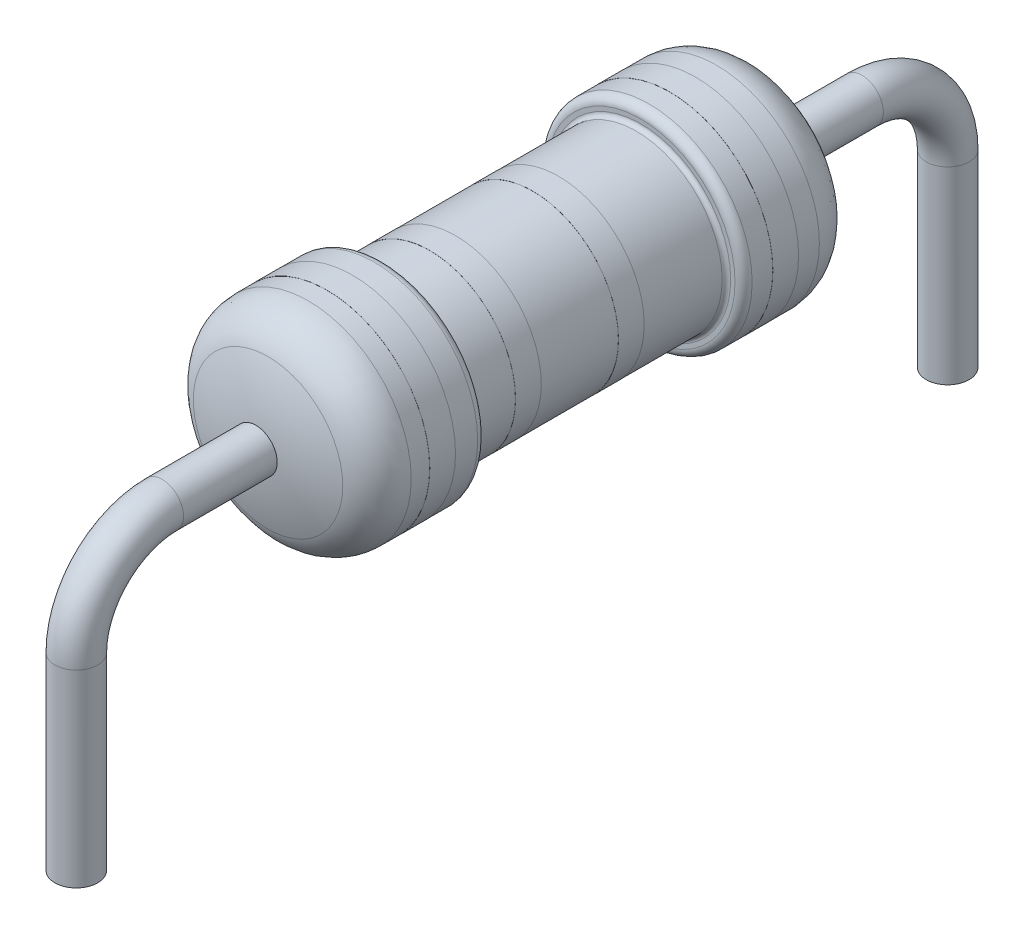
SolidWorks part; units mm, degrees
ref_plane "Plano frontal" through (0, 0, 0) normal (0, 0, 1) x (1, 0, 0)
ref_plane "Plano superior" through (0, 0, 0) normal (0, 1, 0) x (1, 0, 0)
ref_plane "Plano direito" through (0, 0, 0) normal (1, 0, 0) x (0, 0, -1)
sketch "Esboço1" plane through (0, 0, 0) normal (1, 0, 0) x (0, 0, -1)
  line L0 (-13.0537, 0) -> (11.9415, 0) construction
  line L1 (-0.7408, 0.4948) -> (-0.7408, -0.4948) construction
  line L2 (-0.7408, 0) -> (0.7592, 0)
  line L3 (5.2592, -0.5432) -> (5.2592, 0.5432) construction
  line L4 (-0.1156, 1.2) -> (0.6592, 1.2)
  line L5 (0.7592, 1.05) -> (0.7592, 1.1)
  line L6 (-0.7408, 0) -> (0.7592, 1.2) construction
  line L8 (0.8092, 1) -> (3.7092, 1)
  line L9 (-0.5234, 1.0261) -> (0.7592, 0) construction
  line L10 (0.7592, 0) -> (3.7592, 0)
  line L12 (0.7592, 1) -> (3.7592, 0) construction
  line L13 (0.7592, 0) -> (3.7592, 1) construction
  line L14 (3.7592, 0) -> (5.2592, 0)
  line L15 (3.7592, 1.05) -> (3.7592, 1.1)
  line L16 (3.8592, 1.2) -> (4.6432, 1.2)
  line L18 (3.7592, 0) -> (5.0471, 1.0303) construction
  line L19 (3.7592, 1.2) -> (5.2592, 0) construction
  arc A0 (5.1122, 0.8733) -> (4.6432, 1.2) centre (4.6432, 0.7) ccw
  arc A1 (3.7592, 1.1) -> (3.8592, 1.2) centre (3.8592, 1.1) cw
  arc A2 (0.6592, 1.2) -> (0.7592, 1.1) centre (0.6592, 1.1) cw
  arc A3 (-0.5853, 0.8714) -> (-0.1156, 1.2) centre (-0.1156, 0.7) cw
  arc A4 (3.7092, 1) -> (3.7592, 1.05) centre (3.7092, 1.05) ccw
  arc A5 (0.8092, 1) -> (0.7592, 1.05) centre (0.8092, 1.05) cw
  spline S0 degree 3 poles (-0.7408, 0) (-0.7408, 0.1484) (-0.7148, 0.4421) (-0.6371, 0.7294) (-0.5853, 0.8714) knots 0 0 0 0 0.359983 0.719966 0.719966 0.719966 0.719966
  spline S1 degree 3 poles (5.1122, 0.8733) (5.1598, 0.7445) (5.2384, 0.4413) (5.2592, 0.1631) (5.2592, 0) knots 0.299868 0.299868 0.299868 0.299868 0.639755 1 1 1 1
  point P7 (0.0092, 0.6)
  point P11 (2.2592, 0.5)
  point P15 (4.5092, 0.6)
  dimension "D8" = 0.05
  dimension "D4" = 0.5
  dimension "D5" = 0.5
  dimension "D1" = 2.4
  dimension "D2" = 2.4
  dimension "D3" = 2
revolve "Revolução1" add sketch "Esboço1" angle 360 about L0
sketch "Esboço2" plane through (0, 0, 0) normal (1, 0, 0) x (0, 0, -1)
  line L0 (-1.8208, 0) -> (6.3392, 0)
  line L1 (7.3392, -1) -> (7.3392, -3.2)
  line L2 (-2.8208, -1) -> (-2.8208, -3.2)
  line L3 (-0.1156, -1.2) -> (0.6592, -1.2) construction
  arc A0 (6.3392, 0) -> (7.3392, -1) centre (6.3392, -1) cw
  arc A1 (-1.8208, 0) -> (-2.8208, -1) centre (-1.8208, -1) ccw
  point P8 (7.3392, 0)
  point P11 (-2.8208, 0)
  dimension "D3" = 1
  dimension "D1" = 10.16
  dimension "D2" = 2.08
  dimension "D4" = 2
sweep "Varredura1" add path "Esboço2" circular profile diameter 0.5 parameters "D3"=0.5
ref_plane "Plano1" through (0, 0, -0.1) normal (0, 0, 1) x (1, 0, 0)
sketch "Esboço15" plane through (0, 0, -0.1) normal (0, 0, 1) x (1, 0, 0)
  circle A0 centre (0, 0) radius 1.2 construction
  circle A1 centre (0, 0) radius 1.2
sketch "Esboço16" plane through (0, 0, -0.1) normal (0, 0, 1) x (1, 0, 0)
  circle A0 centre (0, 0) radius 1.2 construction
  circle A1 centre (0, 0) radius 1.2
  circle A2 centre (0, 0) radius 1.201
  dimension "D1" = 0.001
extrude "Ressalto-extrusão1" add sketch "Esboço16" against normal blind 0.3
ref_plane "Plano2" through (0, 0, -4.1) normal (0, 0, 1) x (1, 0, 0)
sketch "Esboço17" plane through (0, 0, -4.1) normal (0, 0, 1) x (1, 0, 0)
  circle A0 centre (0, 0) radius 1.2 construction
  circle A1 centre (0, 0) radius 1.2
  circle A2 centre (0, 0) radius 1.201
  dimension "D1" = 0.001
extrude "Ressalto-extrusão2" add sketch "Esboço17" against normal blind 0.3
ref_plane "Plano3" through (0, 0, -1.3) normal (0, 0, 1) x (1, 0, 0)
sketch "Esboço18" plane through (0, 0, -1.3) normal (0, 0, 1) x (1, 0, 0)
  circle A0 centre (0, 0) radius 1 construction
  circle A1 centre (0, 0) radius 1
  circle A2 centre (0, 0) radius 1.001
  dimension "D1" = 0.001
extrude "Ressalto-extrusão3" add sketch "Esboço18" against normal blind 0.3
ref_plane "Plano4" through (0, 0, -2.5) normal (0, 0, 1) x (1, 0, 0)
sketch "Esboço19" plane through (0, 0, -2.5) normal (0, 0, 1) x (1, 0, 0)
  circle A0 centre (0, 0) radius 1 construction
  circle A1 centre (0, 0) radius 1
  circle A2 centre (0, 0) radius 1.001
  dimension "D1" = 0.001
extrude "Ressalto-extrusão6" add sketch "Esboço19" against normal blind 0.3
